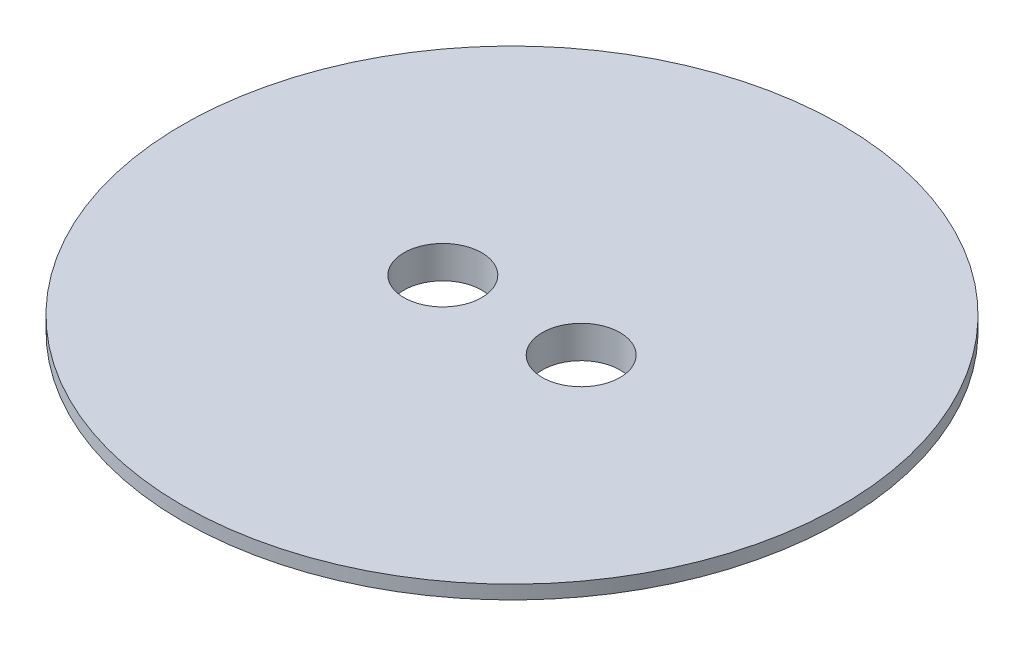
SolidWorks part; units mm, degrees
ref_plane "Front Plane" through (0, 0, 0) normal (0, 0, 1) x (1, 0, 0)
ref_plane "Top Plane" through (0, 0, 0) normal (0, 1, 0) x (1, 0, 0)
ref_plane "Right Plane" through (0, 0, 0) normal (1, 0, 0) x (0, 0, -1)
sketch "Sketch2" plane through (0, 0, 0) normal (0, 1, 0) x (1, 0, 0)
  line L0 (0, 19.3675) -> (0, -19.3675) construction
  circle A0 centre (-4.064, 0) radius 2.286
  circle A1 centre (0, 0) radius 19.3675
  circle A2 centre (4.064, 0) radius 2.286
  dimension "D1" = 38.735
  dimension "D2" = 4.572
  dimension "D3" = 4.064
extrude "Boss-Extrude1" add sketch "Sketch2" along normal blind 1.905 contours L0 A1 A0 | L0 A1
chamfer "Chamfer1" distance 1.905 angle 30 1 edges at (0, 0, 19.3675)
